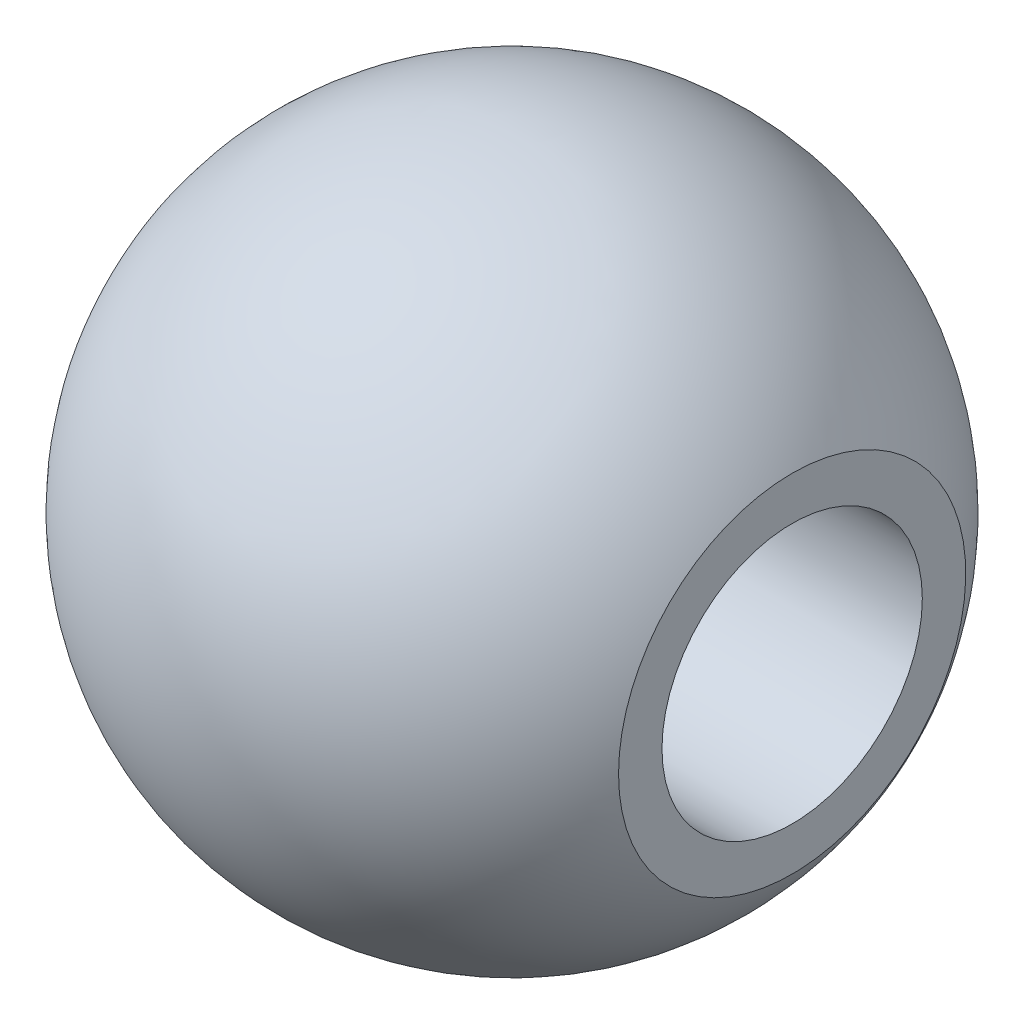
SolidWorks part; units mm, degrees
material "PF"
ref_plane "Front Plane" through (0, 0, 0) normal (0, 0, 1) x (1, 0, 0)
ref_plane "Top Plane" through (0, 0, 0) normal (0, 1, 0) x (1, 0, 0)
ref_plane "Right Plane" through (0, 0, 0) normal (1, 0, 0) x (0, 0, -1)
sketch "Sketch1" plane through (0, 0, 0) normal (0, 0, 1) x (1, 0, 0)
  line L0 (25.8445, 0) -> (-25.8445, 0) construction
  line L1 (46.99, 13.3803) -> (46.99, 10.033)
  line L2 (46.99, 10.033) -> (13.4937, 10.033)
  line L3 (11.9062, 10.033) -> (5.334, 10.033)
  line L4 (5.334, 10.033) -> (5.334, 0)
  line L5 (5.334, 0) -> (0, 0)
  line L6 (0, 0) -> (50.7079, 0) construction
  arc A0 (0, 0) -> (46.99, 13.3803) centre (25.4, 0) cw
  arc A1 (13.4937, 10.033) -> (11.9062, 10.033) centre (12.7, 10.033) ccw
  dimension "D1" = 25.4
  dimension "D6" = 1.5875
  dimension "D2" = 5.334
  dimension "D3" = 10.033
  dimension "D4" = 7.366
  dimension "D5" = 34.29
revolve "Revolve1" add sketch "Sketch1" angle 360 about L6
